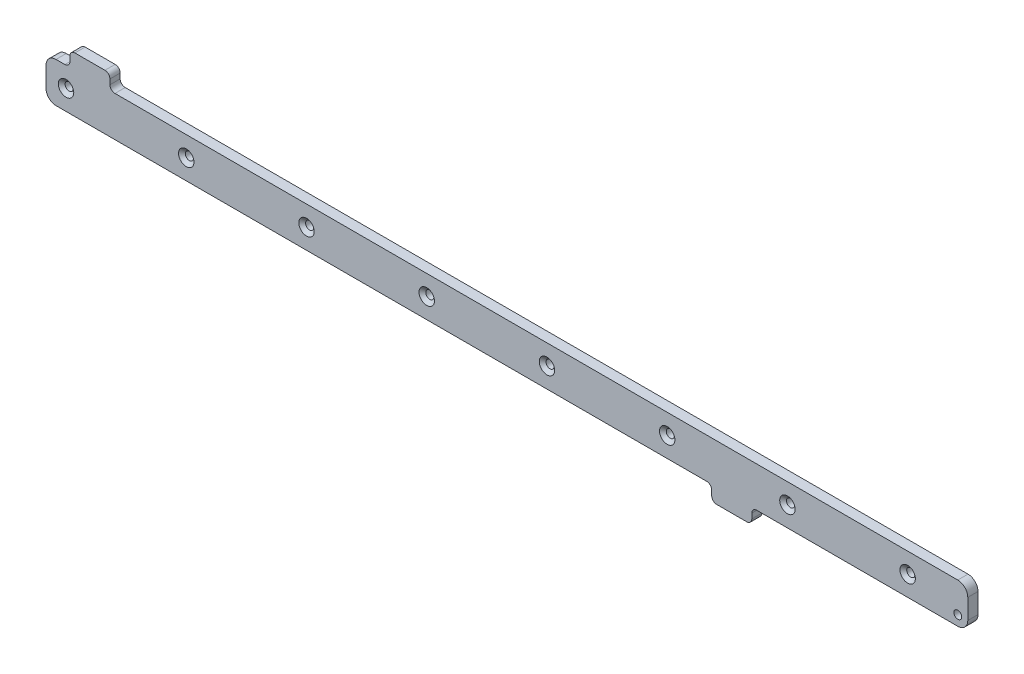
SolidWorks part; units mm, degrees
material "PC High Viscosity"
ref_plane "Front Plane" through (0, 0, 0) normal (0, 0, 1) x (1, 0, 0)
ref_plane "Top Plane" through (0, 0, 0) normal (0, 1, 0) x (1, 0, 0)
ref_plane "Right Plane" through (0, 0, 0) normal (1, 0, 0) x (0, 0, -1)
sketch "Sketch1" plane through (0, 0, 0) normal (0, 0, 1) x (1, 0, 0)
  line L1 (0, 0) -> (40.5308, 0)
  line L2 (0, 0) -> (0, 25.4)
  line L3 (0, 25.4) -> (15.1307, 25.4)
  line L4 (584.2, 0) -> (584.2, 25.4)
  line L5 (15.1307, 34.925) -> (40.5307, 34.925)
  line L6 (40.5307, 34.925) -> (40.5307, 25.4)
  line L7 (15.1307, 34.925) -> (15.1307, 25.4)
  line L11 (584.2, 10.0162) -> (577.85, 13.6823) construction
  line L12 (577.85, 13.6823) -> (571.5, 10.0162) construction
  line L13 (571.5, 10.0162) -> (571.5, 2.6838) construction
  line L14 (571.5, 2.6838) -> (577.85, -0.9823) construction
  line L15 (577.85, -0.9823) -> (584.2, 2.6838) construction
  line L16 (584.2, 2.6838) -> (584.2, 10.0162) construction
  line L19 (40.5307, 25.4) -> (584.2, 25.4)
  line L20 (40.5308, 0) -> (421.9033, 0)
  line L21 (447.3033, 0) -> (447.3033, -9.525)
  line L22 (447.3033, -9.525) -> (421.9033, -9.525)
  line L23 (421.9033, -9.525) -> (421.9033, 0)
  line L24 (447.3033, 0) -> (584.2, 0)
  circle A0 centre (577.85, 6.35) radius 2.4892
  circle A1 centre (577.85, 6.35) radius 6.35 construction
  dimension "D5" = 4.9784
  dimension "D6" = 9.525
  dimension "D7" = 12.7
  dimension "D1" = 584.2
  dimension "D2" = 25.4
  dimension "D3" = 25.4
  dimension "D4" = 40.5307
  dimension "D8" = 421.9033
extrude "Boss-Extrude1" add sketch "Sketch1" along normal blind 6.477
fillet "Fillet2" radius 6.35 4 edges at (0, 0, 3.2385) (0, 25.4, 3.2385) (584.2, 0, 3.2385) (584.2, 25.4, 3.2385)
sketch "Sketch2" plane through (0, 0, 6.477) normal (0, 0, 1) x (1, 0, 0)
  line L0 (6.35, 25.4) -> (15.1307, 25.4) construction
  line L1 (584.2, 19.05) -> (584.2, 6.35) construction
  circle A0 centre (546.1, 12.7) radius 2.0193
  dimension "D1" = 4.0386
  dimension "D2" = 12.7
  dimension "D3" = 38.1
hole_wizard "CSK for #10 Flat Head Machine Screw (100)1" positions "Sketch4" profile "Sketch5" countersink size "#10" standard "ANSI Inch" end condition through all
sketch "Sketch4" plane through (0, 0, 6.477) normal (0, 0, 1) x (1, 0, 0)
  line L0 (584.2, 12.7) -> (0, 12.7) construction
  line L1 (584.2, 19.05) -> (584.2, 6.35) construction
  line L2 (0, 6.35) -> (0, 19.05) construction
  line L3 (6.35, 25.4) -> (15.1307, 25.4) construction
  point P11 (546.1, 12.7)
  dimension "D1" = 12.7
  dimension "D2" = 38.1
sketch "Sketch5" plane through (546.1, 12.7, 6.477) normal (1, 0, 0) x (0, -1, 0)
  line L0 (0, 0) -> (0, 6.477)
  line L1 (0, 6.477) -> (2.5527, 6.477)
  line L2 (2.5527, 6.477) -> (2.5527, 1.9608)
  line L3 (2.5527, 1.9608) -> (4.8895, 0)
  line L5 (4.8895, 0) -> (0, 0)
  line L6 (-2.5527, 1.9608) -> (-4.8895, 0) construction
  line L11 (0, -6.35) -> (0, 107.95) construction
  dimension "Thru Hole Dia." = 5.1054
  dimension "Thru Hole Depth" = 6.477
  dimension "Near C'Sink Dia." = 9.779
  dimension "Near C'Sink Angle" = 100
pattern_linear "LPattern1" count 8 spacing 76.2 along (-1, 0, 0) of "CSK for #10 Flat Head Machine Screw (100)1"
fillet "Fillet3" radius 3.175 8 edges at (15.1307, 25.4, 3.2385) (15.1307, 34.925, 3.2385) (40.5307, 34.925, 3.2385) (40.5307, 25.4, 3.2385) (421.9033, 0, 3.2385) (421.9033, -9.525, 3.2385) (447.3033, -9.525, 3.2385) (447.3033, 0, 3.2385)
